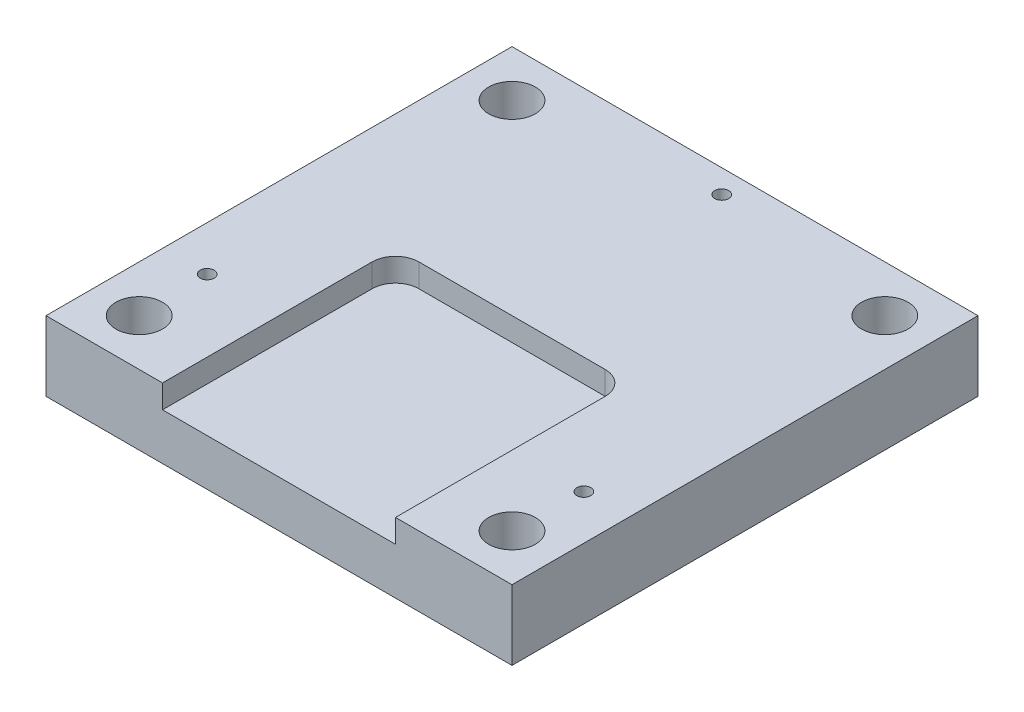
SolidWorks part; units mm, degrees
ref_plane "前视基准面" through (0, 0, 0) normal (0, 0, 1) x (1, 0, 0)
ref_plane "上视基准面" through (0, 0, 0) normal (0, 1, 0) x (1, 0, 0)
ref_plane "右视基准面" through (0, 0, 0) normal (1, 0, 0) x (0, 0, -1)
sketch "草图1" plane through (0, 0, 0) normal (0, 1, 0) x (1, 0, 0)
  line L1 (0, 0) -> (100, 0)
  line L2 (0, 0) -> (0, -100)
  line L3 (0, -100) -> (100, -100)
  line L4 (100, 0) -> (100, -100)
  dimension "D1" = 100
extrude "凸台-拉伸1" add sketch "草图1" along normal blind 15
sketch "草图2" plane through (0, 15, 0) normal (0, 1, 0) x (1, 0, 0)
  line L0 (50, -5) -> (9.5855, -75) construction
  line L1 (9.5855, -75) -> (90.4145, -75) construction
  line L2 (90.4145, -75) -> (50, -5) construction
  line L5 (50, 0) -> (50, -5) construction
  line L6 (100, 0) -> (0, 0) construction
  circle A0 centre (50, -5) radius 1.5
  circle A1 centre (9.5855, -75) radius 1.5
  circle A2 centre (90.4145, -75) radius 1.5
  dimension "D1" = 3
  dimension "D2" = 70
  dimension "D3" = 5
extrude "切除-拉伸1" cut sketch "草图2" against normal through all
sketch "草图3" plane through (0, 15, 0) normal (0, 1, 0) x (1, 0, 0)
  line L0 (9.5855, -75) -> (25, -75) construction
  line L1 (25, -50) -> (75, -50)
  line L2 (25, -50) -> (25, -100)
  line L3 (25, -100) -> (75, -100)
  line L4 (75, -50) -> (75, -100)
  line L6 (75, -75) -> (90.4145, -75) construction
  dimension "D1" = 50
extrude "切除-拉伸2" cut sketch "草图3" against normal blind 5
sketch "草图4" plane through (0, 15, 0) normal (0, 1, 0) x (1, 0, 0)
  line L0 (10, -10) -> (90, -10) construction
  line L1 (90, -10) -> (90, -90) construction
  line L2 (90, -90) -> (10, -90) construction
  line L3 (10, -90) -> (10, -10) construction
  line L4 (50, -90) -> (50, -100) construction
  line L5 (25, -100) -> (75, -100) construction
  line L6 (10, -50) -> (0, -50) construction
  line L7 (0, 0) -> (0, -100) construction
  circle A0 centre (10, -10) radius 5
  circle A1 centre (90, -10) radius 5
  circle A2 centre (10, -90) radius 5
  circle A3 centre (90, -90) radius 5
  dimension "D2" = 10
  dimension "D1" = 80
extrude "切除-拉伸3" cut sketch "草图4" against normal blind 10
fillet "圆角1" radius 5 2 edges at (75, 12.5, 50) (25, 12.5, 50)
